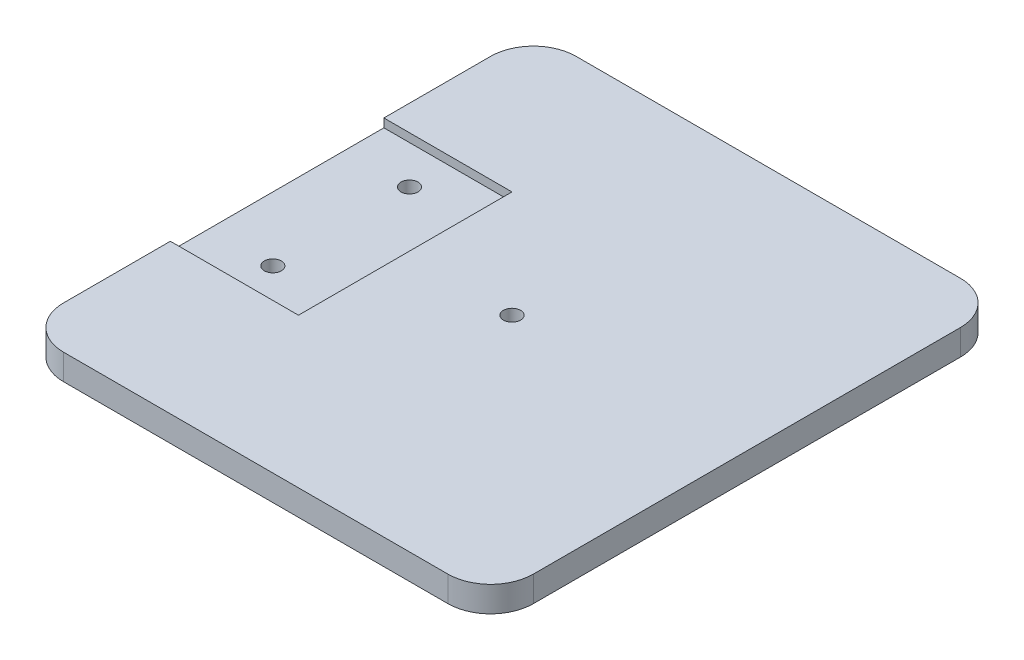
SolidWorks part; units mm, degrees
ref_plane "Front Plane" through (0, 0, 0) normal (0, 0, 1) x (1, 0, 0)
ref_plane "Top Plane" through (0, 0, 0) normal (0, 1, 0) x (1, 0, 0)
ref_plane "Right Plane" through (0, 0, 0) normal (1, 0, 0) x (0, 0, -1)
sketch "Sketch2" plane through (0, 0, 0) normal (0, 1, 0) x (1, 0, 0)
  line L1 (-78.125, 24.375) -> (-23.125, 24.375)
  line L2 (-78.125, 24.375) -> (-78.125, -35.625)
  line L3 (-78.125, -35.625) -> (-23.125, -35.625)
  line L4 (-23.125, 24.375) -> (-23.125, -35.625)
  dimension "D1" = 60
  dimension "D2" = 55
extrude "Boss-Extrude1" add sketch "Sketch2" along normal blind 3
sketch "Sketch3" plane through (0, 3, 0) normal (0, 1, 0) x (1, 0, 0)
  line L0 (-78.125, 24.375) -> (-78.125, -35.625) construction
  line L1 (-78.125, 6.875) -> (-63.125, 6.875)
  line L2 (-78.125, 6.875) -> (-78.125, -18.125)
  line L3 (-78.125, -18.125) -> (-63.125, -18.125)
  line L4 (-63.125, 6.875) -> (-63.125, -18.125)
  line L5 (-23.125, 24.375) -> (-78.125, 24.375) construction
  dimension "D1" = 25
  dimension "D2" = 15
  dimension "D3" = 17.5
extrude "Cut-Extrude1" cut sketch "Sketch3" against normal blind 1
sketch "Sketch4" plane through (0, 3, 0) normal (0, 1, 0) x (1, 0, 0)
  line L0 (-63.125, 6.875) -> (-78.125, 6.875) construction
  line L1 (-78.125, 6.875) -> (-78.125, -18.125) construction
  line L2 (-78.125, -18.125) -> (-63.125, -18.125) construction
  circle A0 centre (-70.625, 2.375) radius 1
  circle A1 centre (-70.625, -13.625) radius 1
  dimension "D2" = 2
  dimension "D4" = 4.5
  dimension "D1" = 4.5
  dimension "D3" = 7.5
extrude "Cut-Extrude3" cut sketch "Sketch4" against normal blind 5
fillet "Fillet1" radius 5 4 edges at (-78.125, 1.5, -24.375) (-23.125, 1.5, -24.375) (-23.125, 1.5, 35.625) (-78.125, 1.5, 35.625)
sketch "Sketch5" plane through (0, 3, 0) normal (0, 1, 0) x (1, 0, 0)
  line L0 (-28.125, 24.375) -> (-73.125, 24.375) construction
  line L1 (-78.125, 19.375) -> (-78.125, 6.875) construction
  circle A0 centre (-50.625, -5.625) radius 1
  dimension "D1" = 30
  dimension "D2" = 27.5
extrude "Cut-Extrude4" cut sketch "Sketch5" against normal blind 5
